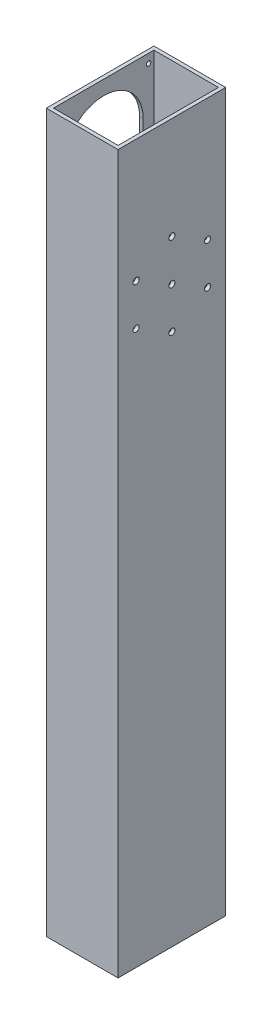
SolidWorks part; units mm, degrees
material "6061-T6 (SS)"
ref_plane "Front Plane" through (0, 0, 0) normal (0, 0, 1) x (1, 0, 0)
ref_plane "Top Plane" through (0, 0, 0) normal (0, 1, 0) x (1, 0, 0)
ref_plane "Right Plane" through (0, 0, 0) normal (1, 0, 0) x (0, 0, -1)
sketch "Sketch1" plane through (0, 0, 0) normal (0, 1, 0) x (1, 0, 0)
  line L0 (2, 2) -> (2, 58)
  line L1 (0, 0) -> (40, 0)
  line L2 (0, 0) -> (0, 60)
  line L3 (0, 60) -> (40, 60)
  line L4 (40, 0) -> (40, 60)
  line L5 (2, 58) -> (38, 58)
  line L6 (38, 2) -> (38, 58)
  line L7 (2, 2) -> (38, 2)
  dimension "D1" = 60
  dimension "D2" = 40
  dimension "D3" = 2
extrude "Boss-Extrude1" add sketch "Sketch1" along normal blind 400
sketch "Sketch2" plane through (40, 0, 0) normal (1, 0, 0) x (0, 0, -1)
  line L1 (0, 400) -> (60, 400) construction
  line L2 (0, 400) -> (0, 340) construction
  line L3 (0, 340) -> (60, 340) construction
  line L4 (60, 400) -> (60, 340) construction
  line L5 (60, 400) -> (60, 0) construction
  line L9 (30, 320) -> (30, 400) construction
  circle A0 centre (30, 320) radius 23
  point P42 (30, 320)
  point P45 (30, 343)
  point P53 (49.9186, 331.5)
  point P54 (49.9186, 308.5)
  point P55 (30, 297)
  point P56 (10.0814, 308.5)
  point P57 (10.0814, 331.5)
  point P69 (30, 320)
  dimension "D1" = 46
  dimension "D2" = 6
  dimension "D3" = 80
hole_wizard "M3 Clearance Hole1" positions "Sketch2" profile "Sketch3" hole size "M3" standard "DIN" end condition through all
sketch "Sketch3" plane through (40, 320, -30) normal (0, 1, 0) x (0, 0, -1)
  line L0 (0, 0) -> (0, 40)
  line L1 (0, 40) -> (1.7, 40)
  line L2 (1.7, 40) -> (1.7, 0)
  line L5 (1.7, 0) -> (0, 0)
  line L11 (0, -6.35) -> (0, 107.95) construction
  dimension "Thru Hole Dia." = 3.4
  dimension "Thru Hole Depth" = 40
sketch "Sketch4" plane through (0, 0, 0) normal (-1, 0, 0) x (0, 0, 1)
  line L0 (-30, 270) -> (-30, 370) construction
  line L1 (-52, 270) -> (-52, 370)
  line L2 (-8, 270) -> (-8, 370)
  arc A0 (-52, 270) -> (-8, 270) centre (-30, 270) ccw
  arc A1 (-8, 370) -> (-52, 370) centre (-30, 370) ccw
  point P2 (-30, 320)
  dimension "D1" = 44
  dimension "D2" = 100
extrude "Cut-Extrude1" cut sketch "Sketch4" against normal blind 3
sketch "Sketch5" plane through (0, 0, 0) normal (-1, 0, 0) x (0, 0, 1)
  line L0 (-58, 400) -> (-58, 0) construction
  line L1 (-58, 400) -> (-58, 0) construction
  line L2 (-52, 370) -> (-58, 370) construction
  line L4 (-55, 400) -> (-55, 230.2967) construction
  line L5 (-60, 400) -> (0, 400) construction
  line L6 (-30, 392) -> (-30, 280.5494) construction
  arc A1 (-52, 270) -> (-8, 270) centre (-30, 270) ccw construction
  arc A2 (-8, 370) -> (-52, 370) centre (-30, 370) ccw construction
  point P13 (-55, 395)
  point P19 (-55, 245)
  point P32 (-55, 345)
  point P33 (-55, 295)
  point P40 (0, 0)
  point P41 (-5, 395)
  point P42 (-5, 345)
  point P43 (-5, 295)
  point P44 (-5, 245)
  dimension "D2" = 25
  dimension "D1" = 5
  dimension "D3" = 3
hole_wizard "Tap Drill for M3 Tap1" positions "Sketch5" profile "Sketch7" hole size "M3" standard "DIN"
sketch "Sketch7" plane through (0, 245, -5) normal (0, 1, 0) x (0, 0, 1)
  line L0 (0, 0) -> (0, 2)
  line L1 (0, 2) -> (1.25, 2)
  line L2 (1.25, 2) -> (1.25, 0.25)
  line L3 (1.25, 0.25) -> (1.5, 0)
  line L5 (1.5, 0) -> (0, 0)
  line L6 (-1.25, 0.25) -> (-1.5, 0) construction
  line L11 (0, -6.35) -> (0, 107.95) construction
  dimension "Thru Hole Dia." = 2.5
  dimension "Thru Hole Depth" = 2
  dimension "Near C'Sink Dia." = 3
  dimension "Near C'Sink Angle" = 90
